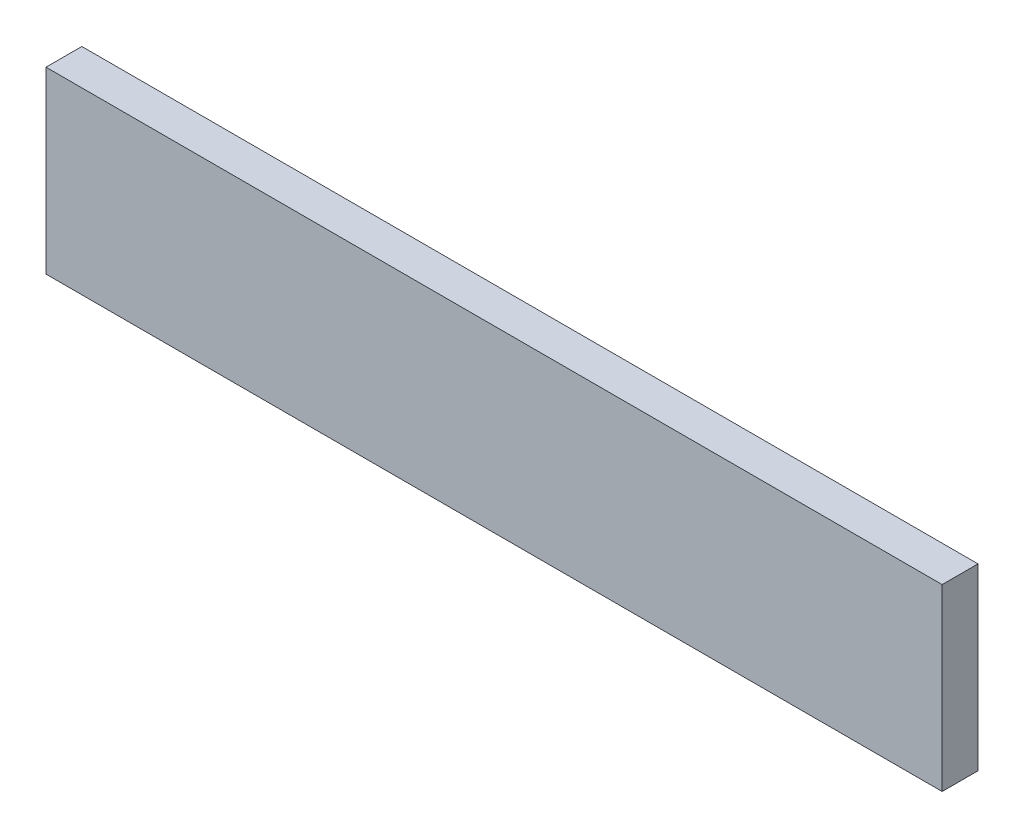
SolidWorks part; units mm, degrees
ref_plane "Front Plane" through (0, 0, 0) normal (0, 0, 1) x (1, 0, 0)
ref_plane "Top Plane" through (0, 0, 0) normal (0, 1, 0) x (1, 0, 0)
ref_plane "Right Plane" through (0, 0, 0) normal (1, 0, 0) x (0, 0, -1)
sketch "Sketch1" plane through (0, 0, 0) normal (0, 0, 1) x (1, 0, 0)
  line L1 (-25, -5) -> (25, -5)
  line L2 (-25, -5) -> (-25, 5)
  line L3 (-25, 5) -> (25, 5)
  line L4 (25, -5) -> (25, 5)
  line L5 (-25, -5) -> (25, 5) construction
  line L6 (-25, 5) -> (25, -5) construction
  point P0 (0, 0)
  dimension "D1" = 50
  dimension "D2" = 10
extrude "Boss-Extrude1" add sketch "Sketch1" along normal blind 2
